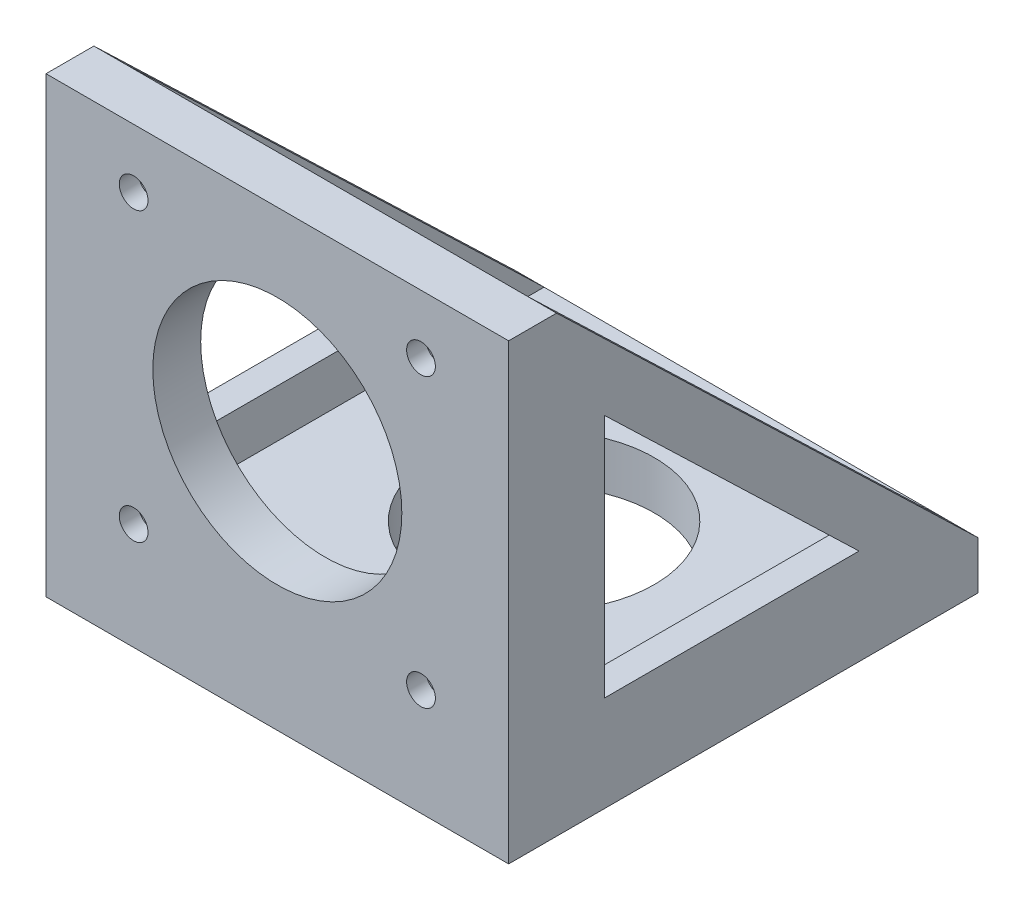
SolidWorks part; units mm, degrees
ref_plane "Front Plane" through (0, 0, 0) normal (0, 0, 1) x (1, 0, 0)
ref_plane "Top Plane" through (0, 0, 0) normal (0, 1, 0) x (1, 0, 0)
ref_plane "Right Plane" through (0, 0, 0) normal (1, 0, 0) x (0, 0, -1)
sketch "Sketch1" plane through (0, 0, 0) normal (0, 1, 0) x (1, 0, 0)
  line L0 (-21.15, -17.8) -> (21.15, -17.8) construction
  line L5 (-21.15, 24.5) -> (21.15, 24.5)
  line L6 (-21.15, 24.5) -> (-21.15, -24.5)
  line L7 (-21.15, -24.5) -> (21.15, -24.5)
  line L8 (21.15, 24.5) -> (21.15, -24.5)
  line L9 (0, -24.5) -> (0, 24.5) construction
  line L10 (-21.15, 0) -> (21.15, 0) construction
  line L11 (21.15, -17.8) -> (-21.15, 24.5) construction
  line L12 (21.15, 24.5) -> (-21.15, -17.8) construction
  line L13 (0, 3.35) -> (21.15, 3.35) construction
  circle A2 centre (-15.5, 18.85) radius 1.5
  circle A3 centre (15.5, 18.85) radius 1.5
  circle A4 centre (-15.5, -12.15) radius 1.5
  circle A5 centre (15.5, -12.15) radius 1.5
  circle A6 centre (0, 3.35) radius 11.5
  point P0 (0, 0)
  dimension "D4" = 31
  dimension "D5" = 3
  dimension "D6" = 23
  dimension "D1" = 49
  dimension "D2" = 42.3
  dimension "D3" = 42.3
extrude "Boss-Extrude1" add sketch "Sketch1" along normal blind 5
sketch "Sketch2" plane through (0, 5, 0) normal (0, 1, 0) x (1, 0, 0)
  line L0 (21.15, -24.5) -> (21.15, 24.5) construction
  line L1 (-21.15, -24.5) -> (21.15, -24.5)
  line L2 (-21.15, -24.5) -> (-21.15, -19.5)
  line L3 (-21.15, -19.5) -> (21.15, -19.5)
  line L4 (21.15, -24.5) -> (21.15, -19.5)
  dimension "D1" = 5
extrude "Boss-Extrude2" add sketch "Sketch2" along normal blind 42.3
sketch "Sketch4" plane through (0, 0, 19.5) normal (0, 0, -1) x (-1, 0, 0)
  line L0 (-21.15, 47.3) -> (21.15, 5) construction
  line L1 (21.15, 47.3) -> (-21.15, 5) construction
  line L2 (0, 26.15) -> (21.15, 26.15) construction
  line L3 (21.15, 47.3) -> (21.15, 5) construction
  circle A0 centre (-15, 41.15) radius 1.5
  circle A1 centre (15, 41.15) radius 1.5
  circle A2 centre (-15, 11.15) radius 1.5
  circle A3 centre (15, 11.15) radius 1.5
  circle A4 centre (0, 26.15) radius 13
  dimension "D2" = 3
  dimension "D3" = 26
  dimension "D1" = 30
extrude "Cut-Extrude1" cut sketch "Sketch4" against normal through all
sketch "Sketch5" plane through (21.15, 0, 0) normal (1, 0, 0) x (0, 0, -1)
  line L0 (-19.5, 47.3) -> (24.5, 5)
  line L1 (24.5, 5) -> (24.5, 0)
  line L2 (24.5, 0) -> (-24.5, 0)
  line L3 (-24.5, 0) -> (-24.5, 47.3)
  line L4 (-24.5, 47.3) -> (-19.5, 47.3)
extrude "Boss-Extrude3" add sketch "Sketch5" along normal blind 3
sketch "Sketch6" plane through (-21.15, 0, 0) normal (-1, 0, 0) x (0, 0, 1)
  line L5 (19.5, 47.3) -> (-24.5, 5)
  line L6 (-24.5, 5) -> (-24.5, 0)
  line L7 (-24.5, 0) -> (24.5, 0)
  line L8 (24.5, 0) -> (24.5, 47.3)
  line L9 (24.5, 47.3) -> (19.5, 47.3)
  line L10 (19.5, 47.3) -> (-24.5, 5)
  line L11 (-24.5, 5) -> (-24.5, 0)
  line L12 (-24.5, 0) -> (24.5, 0)
  line L13 (24.5, 0) -> (24.5, 47.3)
  line L14 (24.5, 47.3) -> (19.5, 47.3)
  dimension "D1" = 0
extrude "Boss-Extrude4" add sketch "Sketch6" along normal blind 3
sketch "Sketch8" plane through (0, 0, 19.5) normal (0, 0, -1) x (-1, 0, 0)
  circle A0 centre (-15, 41.15) radius 3
  circle A1 centre (15, 41.15) radius 3
  circle A2 centre (15, 11.15) radius 3
  circle A3 centre (-15, 11.15) radius 3
  dimension "D1" = 6
extrude "Cut-Extrude2" cut sketch "Sketch8" against normal blind 3
sketch "Sketch9" plane through (-24.15, 0, 0) normal (-1, 0, 0) x (0, 0, 1)
  line L0 (-12.0845, 10) -> (14.5, 35.5574)
  line L1 (14.5, 35.5574) -> (14.5, 10)
  line L2 (14.5, 10) -> (-12.0845, 10)
  line L3 (19.5, 47.3) -> (-24.5, 5) construction
  line L4 (24.5, 0) -> (24.5, 47.3) construction
  line L5 (-24.5, 0) -> (24.5, 0) construction
  dimension "D1" = 5
  dimension "D2" = 10
  dimension "D3" = 10
extrude "Cut-Extrude3" cut sketch "Sketch9" against normal through all
